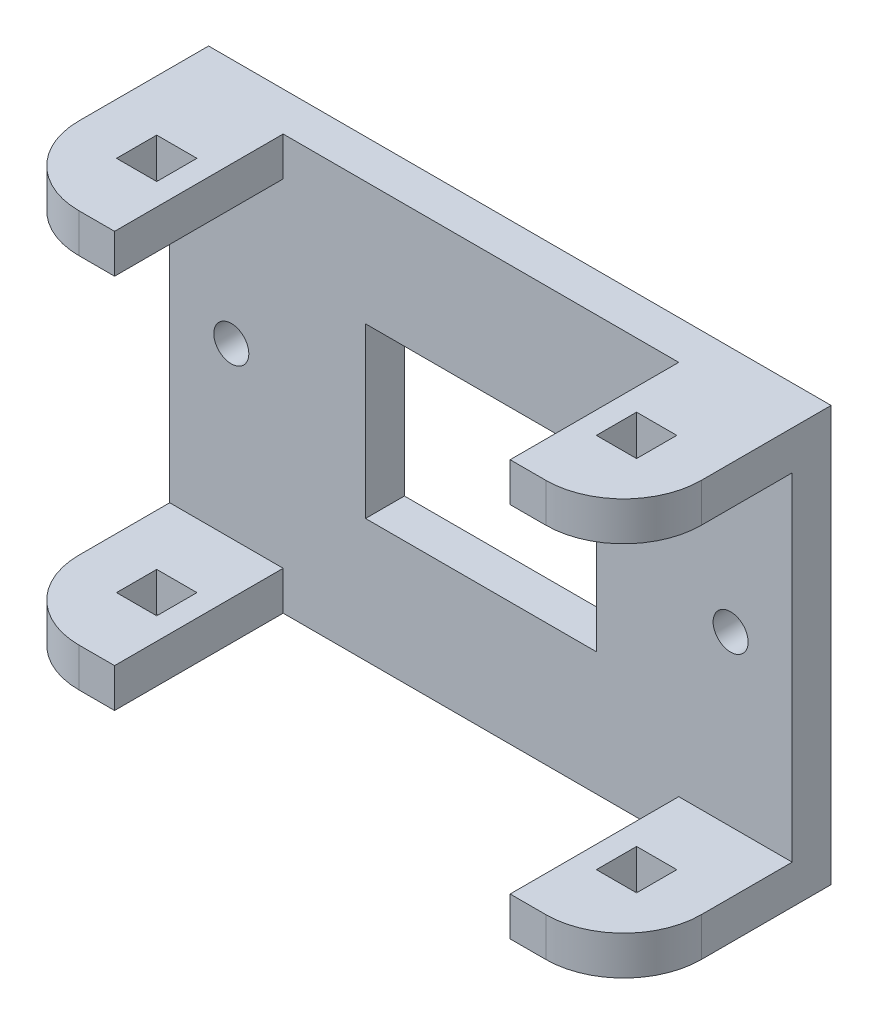
SolidWorks part; units mm, degrees
ref_plane "Frontal" through (0, 0, 0) normal (0, 0, 1) x (1, 0, 0)
ref_plane "Superior" through (0, 0, 0) normal (0, 1, 0) x (1, 0, 0)
ref_plane "Direito" through (0, 0, 0) normal (1, 0, 0) x (0, 0, -1)
sketch "Esboço6" plane through (0, 0, 0) normal (0, 0, 1) x (1, 0, 0)
  line L1 (-8.9, 6.5) -> (8.9, 6.5)
  line L2 (-8.9, 6.5) -> (-8.9, -6.5)
  line L3 (-8.9, -6.5) -> (8.9, -6.5)
  line L4 (8.9, 6.5) -> (8.9, -6.5)
  line L5 (-8.9, 6.5) -> (8.9, -6.5) construction
  line L6 (-8.9, -6.5) -> (8.9, 6.5) construction
  line L7 (-24, 16) -> (24, 16)
  line L8 (-24, 16) -> (-24, -16)
  line L9 (-24, -16) -> (24, -16)
  line L10 (24, 16) -> (24, -16)
  line L11 (-24, 16) -> (24, -16) construction
  line L12 (-24, -16) -> (24, 16) construction
  point P0 (0, 0)
  point P5 (0, 0)
extrude "Ressalto-extrusão2" add sketch "Esboço6" along normal blind 3
sketch "Esboço7" plane through (0, 0, 3) normal (0, 0, 1) x (1, 0, 0)
  line L0 (19.25, 0) -> (-19.25, 0) construction
  line L1 (0, 0) -> (0, -13.7164) construction
  circle A0 centre (-19.25, 0) radius 1.35
  circle A1 centre (19.25, 0) radius 1.35
extrude "Corte-extrusão3" cut sketch "Esboço7" against normal through all
sketch "Esboço8" plane through (0, 0, 3) normal (0, 0, 1) x (1, 0, 0)
  line L0 (24, -16) -> (24, 16) construction
  line L1 (-24, -16) -> (24, -16)
  line L2 (-24, -16) -> (-24, -13)
  line L3 (-24, -13) -> (24, -13)
  line L4 (24, -16) -> (24, -13)
  line L5 (0, 0) -> (22.8866, 0) construction
  line L6 (24, 16) -> (24, 13)
  line L7 (-24, 13) -> (24, 13)
  line L8 (-24, 16) -> (-24, 13)
  line L9 (-24, 16) -> (24, 16)
extrude "Ressalto-extrusão3" add sketch "Esboço8" along normal blind 13
sketch "Esboço10" plane through (0, 13, 0) normal (0, -1, 0) x (1, 0, 0)
  line L0 (24, 3) -> (24, 9.5) construction
  line L1 (24, 9.5) -> (-24, 9.5) construction
  line L2 (-24, 16) -> (-24, 3) construction
  line L3 (-24, 3) -> (24, 3) construction
  line L4 (24, 16) -> (24, 3) construction
  line L5 (-18.5, 9.5) -> (18.5, 9.5) construction
  line L6 (0, 9.5) -> (0, 3) construction
  line L7 (16.95, 11.05) -> (20.05, 11.05)
  line L8 (16.95, 11.05) -> (16.95, 7.95)
  line L9 (16.95, 7.95) -> (20.05, 7.95)
  line L10 (20.05, 11.05) -> (20.05, 7.95)
  line L11 (16.95, 11.05) -> (20.05, 7.95) construction
  line L12 (16.95, 7.95) -> (20.05, 11.05) construction
  line L13 (-16.95, 7.95) -> (-20.05, 11.05) construction
  line L14 (-16.95, 11.05) -> (-20.05, 7.95) construction
  line L15 (-24, 3) -> (-24, 9.5) construction
  line L16 (-20.05, 11.05) -> (-20.05, 7.95)
  line L17 (-16.95, 7.95) -> (-20.05, 7.95)
  line L18 (-16.95, 11.05) -> (-16.95, 7.95)
  line L19 (-16.95, 11.05) -> (-20.05, 11.05)
extrude "Corte-extrusão4" cut sketch "Esboço10" against normal through all and the other way through all
sketch "Esboço11" plane through (0, 13, 0) normal (0, -1, 0) x (1, 0, 0)
  line L0 (-18.5, 7.95) -> (-18.5, 11.05) construction
  line L1 (-16.95, 7.95) -> (-20.05, 7.95) construction
  line L2 (-20.05, 11.05) -> (-16.95, 11.05) construction
  line L3 (18.5, 7.95) -> (18.5, 11.05) construction
  line L4 (20.05, 7.95) -> (16.95, 7.95) construction
  line L5 (16.95, 11.05) -> (20.05, 11.05) construction
  line L6 (18.5, 9.5) -> (-18.5, 9.5) construction
  line L7 (-24, 16) -> (24, 16) construction
  line L8 (-15.25, 3) -> (15.25, 3)
  line L9 (-15.25, 3) -> (-15.25, 16)
  line L10 (-15.25, 16) -> (15.25, 16)
  line L11 (15.25, 3) -> (15.25, 16)
  line L12 (-15.25, 3) -> (15.25, 16) construction
  line L13 (-15.25, 16) -> (15.25, 3) construction
  point P14 (0, 9.5)
  dimension "D1" = 30.5
extrude "Corte-extrusão5" cut sketch "Esboço11" against normal through all and the other way through all
fillet "Filete1" radius 6 1 edges at (24, -14.5, 16)
fillet "Filete2" radius 6 1 edges at (24, 14.5, 16)
fillet "Filete3" radius 6 2 edges at (-24, 14.5, 16) (-24, -14.5, 16)
